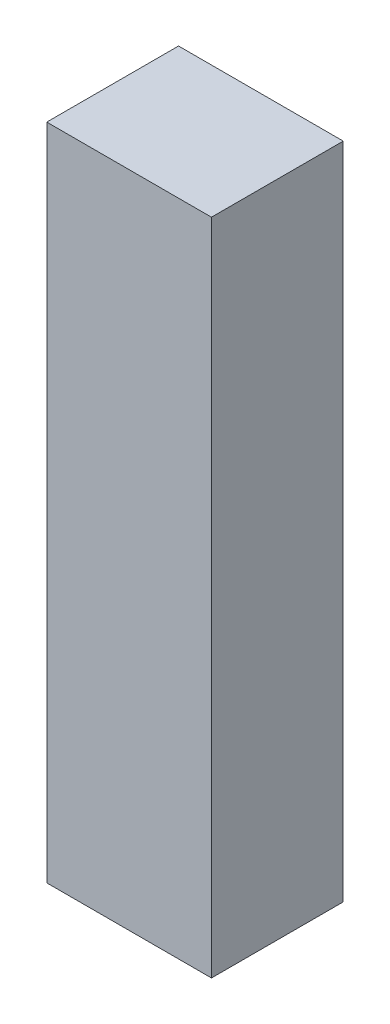
SolidWorks part; units mm, degrees
ref_plane "Front Plane" through (0, 0, 0) normal (0, 0, 1) x (1, 0, 0)
ref_plane "Top Plane" through (0, 0, 0) normal (0, 1, 0) x (1, 0, 0)
ref_plane "Right Plane" through (0, 0, 0) normal (1, 0, 0) x (0, 0, -1)
other "Configuration Table"
sketch "Sketch1" plane through (0, 0, 0) normal (0, 0, 1) x (1, 0, 0)
  line L1 (520, 330) -> (570, 330)
  line L2 (520, 330) -> (520, 530)
  line L3 (520, 530) -> (570, 530)
  line L4 (570, 330) -> (570, 530)
extrude "TOPPING_arka_duvar_pano_surucu_6_1" add sketch "Sketch1" against normal blind 40 from offset 736 separate body
